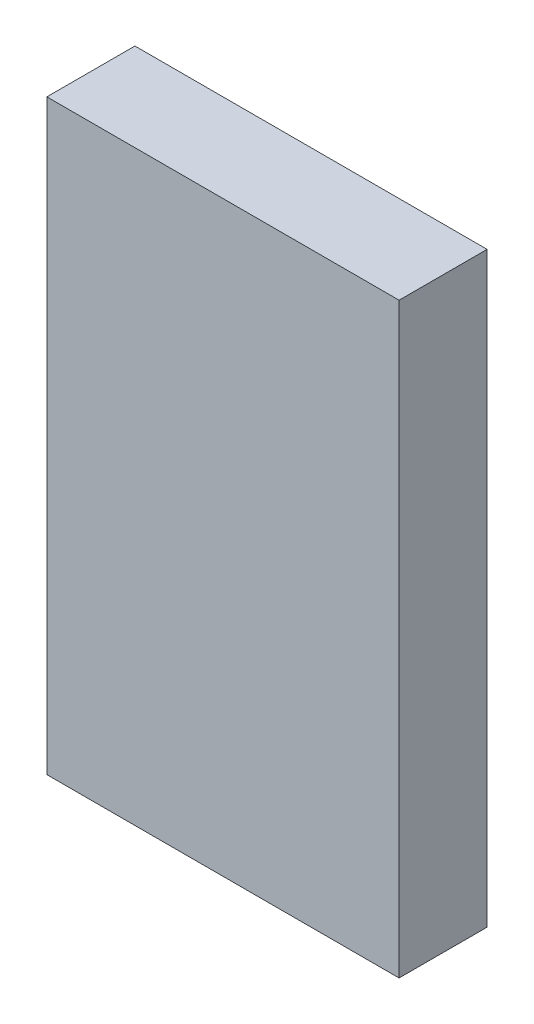
SolidWorks part; units mm, degrees
ref_plane "Front Plane" through (0, 0, 0) normal (0, 0, 1) x (1, 0, 0)
ref_plane "Top Plane" through (0, 0, 0) normal (0, 1, 0) x (1, 0, 0)
ref_plane "Right Plane" through (0, 0, 0) normal (1, 0, 0) x (0, 0, -1)
sketch "Sketch1" plane through (0, 0, 0) normal (0, 0, 1) x (1, 0, 0)
  line L1 (0, 0) -> (19.05, 0)
  line L2 (0, 0) -> (0, 31.75)
  line L3 (0, 31.75) -> (19.05, 31.75)
  line L4 (19.05, 0) -> (19.05, 31.75)
  dimension "D1" = 19.05
  dimension "D2" = 31.75
extrude "Boss-Extrude1" add sketch "Sketch1" along normal blind 4.7625
